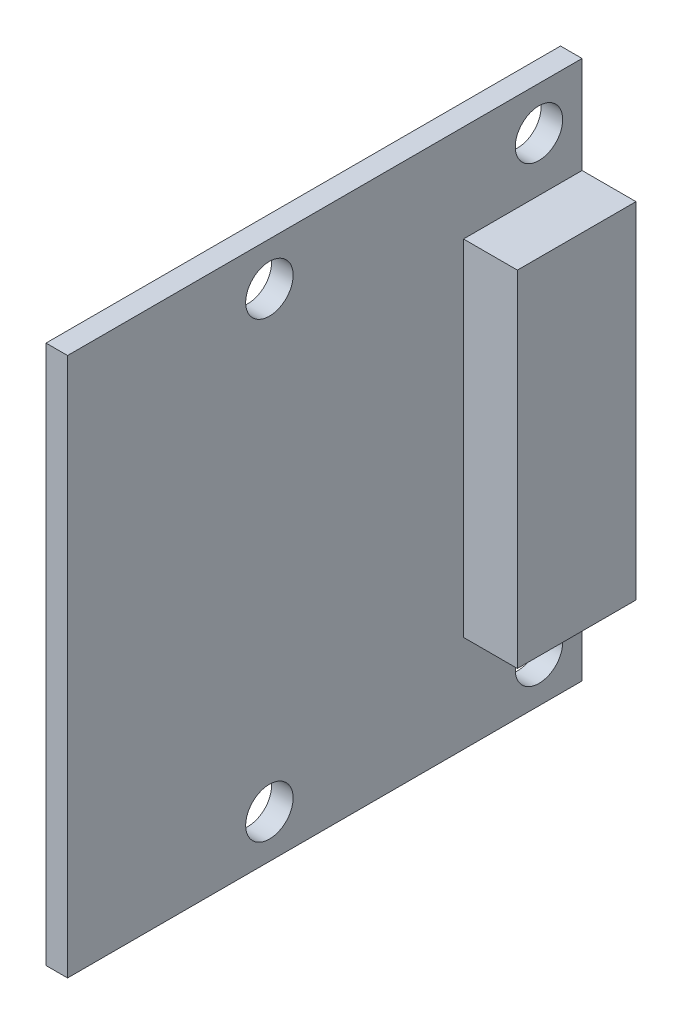
SolidWorks part; units mm, degrees
ref_plane "Alzado" through (0, 0, 0) normal (0, 0, 1) x (1, 0, 0)
ref_plane "Planta" through (0, 0, 0) normal (0, 1, 0) x (1, 0, 0)
ref_plane "Vista lateral" through (0, 0, 0) normal (1, 0, 0) x (0, 0, -1)
ref_plane "Plano1" through (-16.9, 0, 0) normal (1, 0, 0) x (0, 0, -1)
sketch "Croquis1" plane through (-16.9, 0, 0) normal (1, 0, 0) x (0, 0, -1)
  line L0 (-82.5, -12.5) -> (-82.5, 12.5)
  line L1 (-82.5, 12.5) -> (-106.36, 12.5)
  line L2 (-106.36, 12.5) -> (-106.36, -12.5)
  line L3 (-106.36, -12.5) -> (-82.5, -12.5)
extrude "Saliente-Extruir1" add sketch "Croquis1" along normal blind 1
ref_plane "Plano2" through (-17.9, 0, 0) normal (1, 0, 0) x (0, 0, -1)
sketch "Croquis2" plane through (-17.9, 0, 0) normal (1, 0, 0) x (0, 0, -1)
  circle A0 centre (-97, -10.5) radius 1.1
  circle A1 centre (-84.5, -10.5) radius 1.1
  circle A2 centre (-97, 10.5) radius 1.1
  circle A3 centre (-84.5, 10.5) radius 1.1
extrude "Cortar-Extruir1" cut sketch "Croquis2" along normal blind 3
ref_plane "Plano3" through (-21.4, 0, 0) normal (1, 0, 0) x (0, 0, -1)
sketch "Croquis3" plane through (-21.4, 0, 0) normal (1, 0, 0) x (0, 0, -1)
  line L0 (-92.75, -4.25) -> (-92.75, 4.25)
  line L1 (-92.75, 4.25) -> (-101.25, 4.25)
  line L2 (-101.25, 4.25) -> (-101.25, -4.25)
  line L3 (-101.25, -4.25) -> (-92.75, -4.25)
extrude "Saliente-Extruir2" add sketch "Croquis3" along normal blind 4.5
ref_plane "Plano4" through (-15.9, 0, 0) normal (1, 0, 0) x (0, 0, -1)
sketch "Croquis4" plane through (-15.9, 0, 0) normal (1, 0, 0) x (0, 0, -1)
  line L0 (-82.5, -8) -> (-82.5, 8)
  line L1 (-82.5, 8) -> (-88, 8)
  line L2 (-88, 8) -> (-88, -8)
  line L3 (-88, -8) -> (-82.5, -8)
extrude "Saliente-Extruir3" add sketch "Croquis4" along normal blind 2.5
